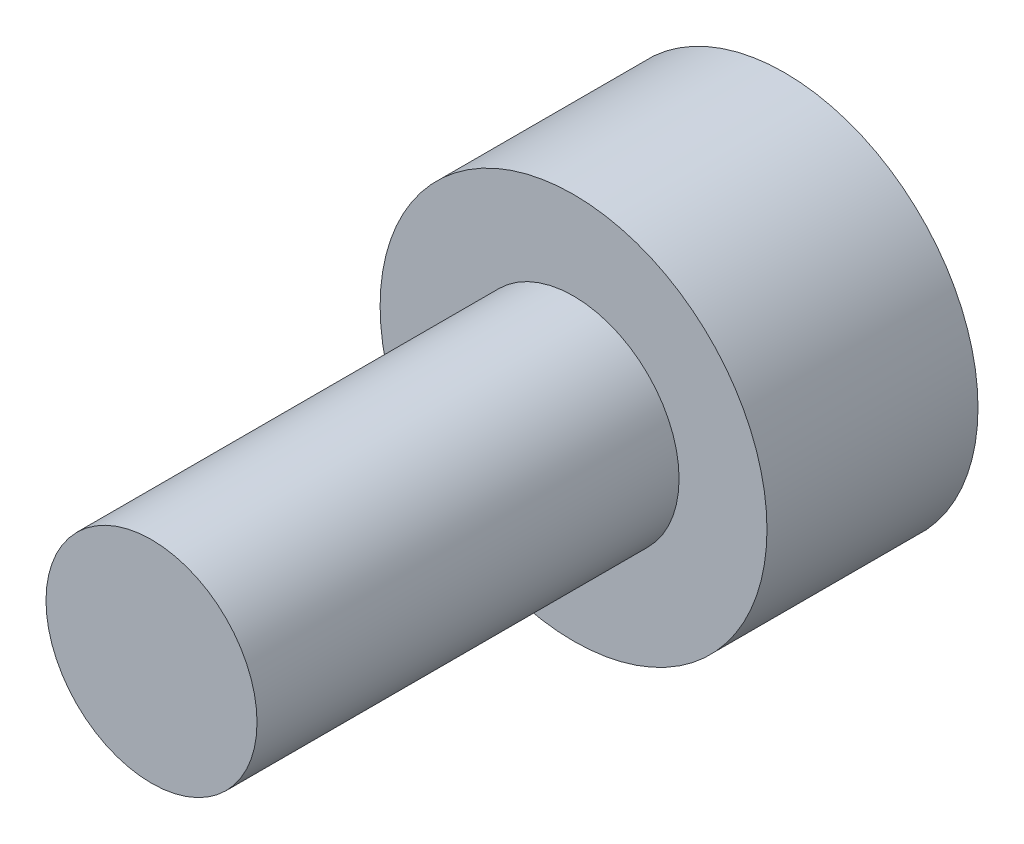
SolidWorks part; units mm, degrees
other "DetailItem1"
material "Chrome Stainless Steel"
ref_plane "Front Plane" through (0, 0, 0) normal (0, 0, 1) x (1, 0, 0)
ref_plane "Top Plane" through (0, 0, 0) normal (0, 1, 0) x (1, 0, 0)
ref_plane "Right Plane" through (0, 0, 0) normal (1, 0, 0) x (0, 0, -1)
sketch "Sketch1" plane through (0, 0, 0) normal (0, 0, 1) x (1, 0, 0)
  circle A0 centre (0, 0) radius 1.5
  dimension "OD" = 3
extrude "Extrude1" add sketch "Sketch1" against normal blind 6
sketch "Sketch6" plane through (0, 0, -6) normal (0, 0, -1) x (-1, 0, 0)
  circle A0 centre (0, 0) radius 2.75
  dimension "head dia" = 5.5
extrude "Extrude2" add sketch "Sketch6" along normal blind 3
sketch "Sketch7" plane through (0, 0, -9) normal (0, 0, -1) x (-1, 0, 0)
  line L1 (0, 1.4434) -> (-1.25, 0.7217)
  line L2 (-1.25, 0.7217) -> (-1.25, -0.7217)
  line L3 (-1.25, -0.7217) -> (0, -1.4434)
  line L4 (0, -1.4434) -> (1.25, -0.7217)
  line L5 (1.25, -0.7217) -> (1.25, 0.7217)
  line L6 (1.25, 0.7217) -> (0, 1.4434)
  circle A0 centre (0, 0) radius 1.25 construction
  dimension "hex dia" = 2.5
extrude "Cut-Extrude1" cut sketch "Sketch7" against normal blind 1.875
equation "\"D1@Cut-Extrude1\" = \"hex dia@Sketch7\"*.75"
